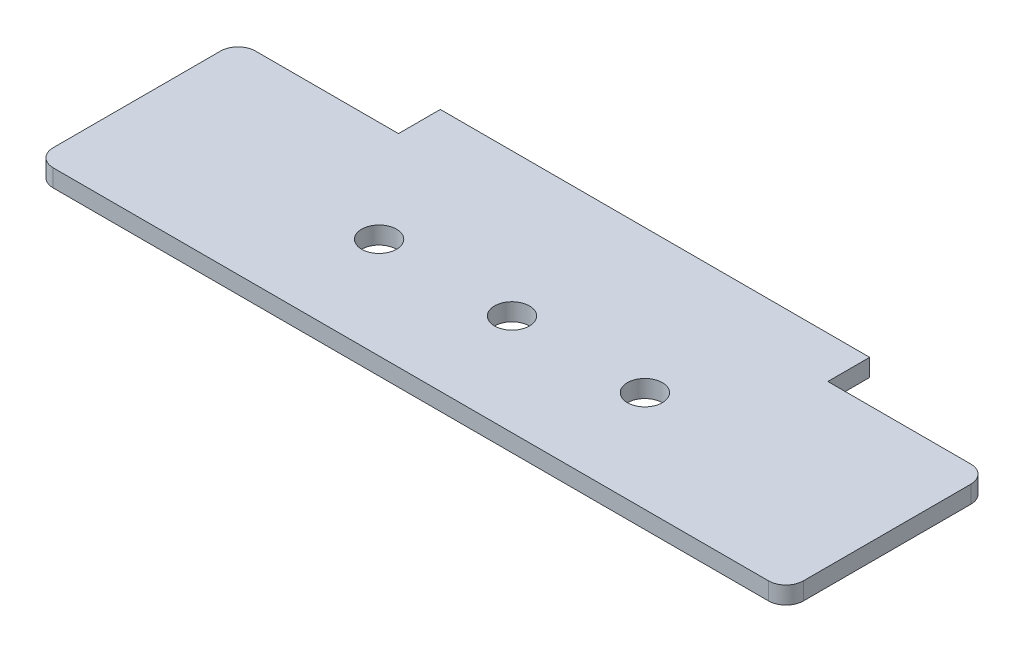
SolidWorks part; units mm, degrees
ref_plane "Front Plane" through (0, 0, 0) normal (0, 0, 1) x (1, 0, 0)
ref_plane "Top Plane" through (0, 0, 0) normal (0, 1, 0) x (1, 0, 0)
ref_plane "Right Plane" through (0, 0, 0) normal (1, 0, 0) x (0, 0, -1)
sketch "Sketch1" plane through (0, 0, 0) normal (0, 1, 0) x (1, 0, 0)
  line L0 (9.965, 2.9) -> (14.065, 2.9)
  line L1 (-6.445, 2.9) -> (-2.345, 2.9)
  line L2 (-6.945, 2.4) -> (-6.945, -2.4)
  line L3 (-6.445, -2.9) -> (14.065, -2.9)
  line L4 (14.565, 2.4) -> (14.565, -2.4)
  line L5 (-2.345, 4.1) -> (9.965, 4.1)
  line L6 (-2.345, 4.1) -> (-2.345, 2.9)
  line L8 (9.965, 4.1) -> (9.965, 2.9)
  line L9 (-6.945, 0) -> (14.565, 0) construction
  circle A0 centre (0, 0) radius 0.5
  circle A1 centre (3.81, 0) radius 0.5
  circle A2 centre (7.62, 0) radius 0.5
  arc A4 (-6.445, 2.9) -> (-6.945, 2.4) centre (-6.445, 2.4) ccw
  arc A5 (14.065, 2.9) -> (14.565, 2.4) centre (14.065, 2.4) cw
  arc A6 (14.065, -2.9) -> (14.565, -2.4) centre (14.065, -2.4) ccw
  arc A7 (-6.945, -2.4) -> (-6.445, -2.9) centre (-6.445, -2.4) ccw
  point P18 (0, 0)
  point P19 (0, 0)
  point P20 (3.81, 0)
  point P25 (-6.945, 2.9)
  point P30 (14.565, -2.9)
  point P33 (-6.945, -2.9)
  dimension "D6" = 1
  dimension "D8" = 3.81
  dimension "D9" = 12.31
  dimension "D11" = 0.5
  dimension "D2" = 5.8
  dimension "D3" = 4.6
  dimension "D4" = 4.6
  dimension "D5" = 7
  dimension "D7" = 3.81
extrude "Boss-Extrude1" add sketch "Sketch1" along normal blind 0.5
